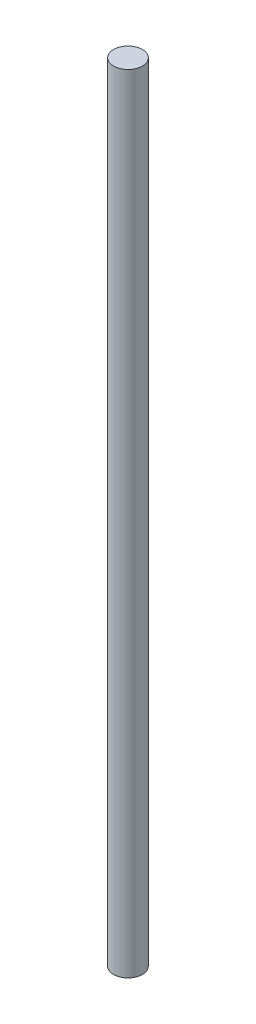
SolidWorks part; units mm, degrees
ref_plane "Front" through (0, 0, 0) normal (0, 0, 1) x (1, 0, 0)
ref_plane "Top" through (0, 0, 0) normal (0, 1, 0) x (1, 0, 0)
ref_plane "Right" through (0, 0, 0) normal (1, 0, 0) x (0, 0, -1)
sketch "Sketch1" plane through (0, 0, 0) normal (0, 1, 0) x (1, 0, 0)
  circle A0 centre (0, 0) radius 2.032
  dimension "D1" = 4.064
extrude "Boss-Extrude1" add sketch "Sketch1" along normal mid plane 110.998
